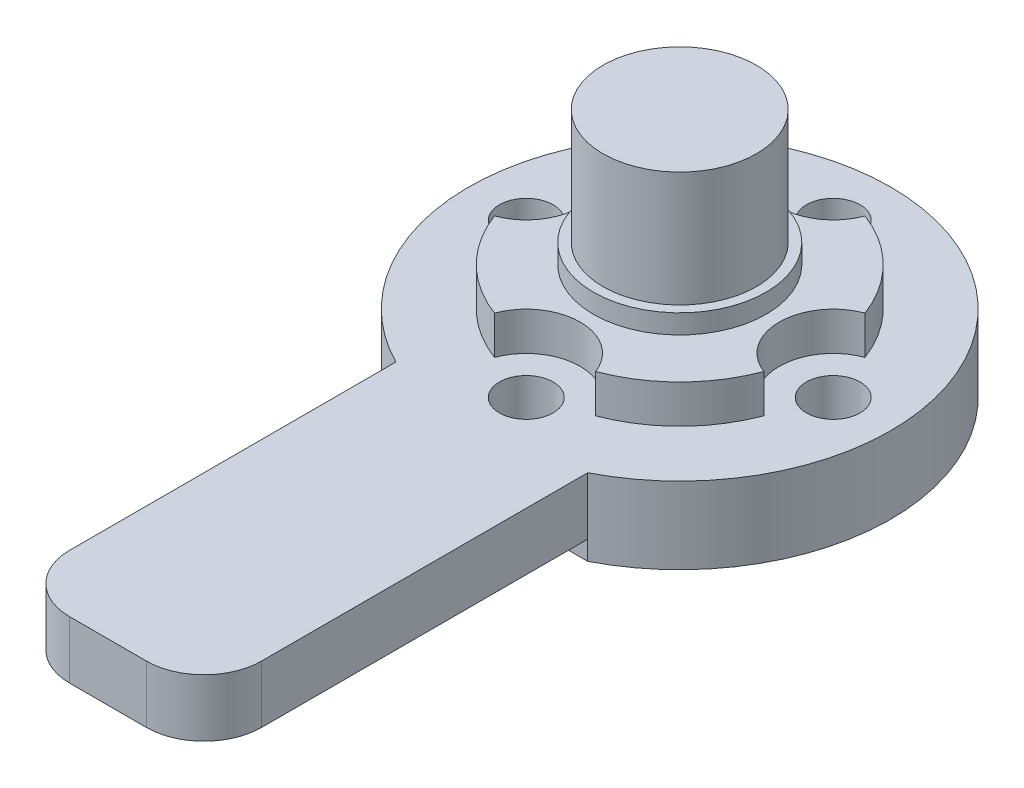
SolidWorks part; units mm, degrees
ref_plane "Front Plane" through (0, 0, 0) normal (0, 0, 1) x (1, 0, 0)
ref_plane "Top Plane" through (0, 0, 0) normal (0, 1, 0) x (1, 0, 0)
ref_plane "Right Plane" through (0, 0, 0) normal (1, 0, 0) x (0, 0, -1)
sketch "Sketch1" plane through (0, 0, 0) normal (0, 1, 0) x (1, 0, 0)
  circle A0 centre (0, 0) radius 11
  circle A1 centre (0, 0) radius 4.25
  dimension "D1" = 22
  dimension "D2" = 8.5
extrude "Boss-Extrude1" add sketch "Sketch1" along normal blind 4
sketch "Sketch2" plane through (0, 4, 0) normal (0, 1, 0) x (1, 0, 0)
  circle A0 centre (0, 8) radius 1.4
  circle A1 centre (8, 0) radius 1.4
  circle A2 centre (0, -8) radius 1.4
  circle A3 centre (-8, 0) radius 1.4
  point P19 (0, 0)
  dimension "D1" = 2.8
  dimension "D2" = 8
  dimension "D3" = 4
extrude "Cut-Extrude1" cut sketch "Sketch2" against normal through all
sketch "Sketch3" plane through (0, 4, 0) normal (0, 1, 0) x (1, 0, 0)
  circle A0 centre (0, 0) radius 7.5
  dimension "D1" = 15
extrude "Boss-Extrude2" add sketch "Sketch3" along normal blind 2
sketch "Sketch4" plane through (0, 6, 0) normal (0, 1, 0) x (1, 0, 0)
  circle A0 centre (8, 0) radius 2.8111
  circle A1 centre (0, -8) radius 2.8111
  circle A2 centre (-8, 0) radius 2.8111
  circle A3 centre (0, 8) radius 2.8111
  point P12 (0, 0)
  dimension "D1" = 4
extrude "Cut-Extrude2" cut sketch "Sketch4" against normal up to surface (2 mm away) up to face at (0, 4, 0)
sketch "Sketch5" plane through (0, 6, 0) normal (0, 1, 0) x (1, 0, 0)
  circle A0 centre (0, 0) radius 4.5
  dimension "D1" = 9
extrude "Boss-Extrude3" add sketch "Sketch5" along normal blind 7
sketch "Sketch6" plane through (0, 13, 0) normal (0, 1, 0) x (1, 0, 0)
  circle A0 centre (0, 0) radius 4
  circle A1 centre (0, 0) radius 4.5
  dimension "D1" = 8
extrude "Cut-Extrude3" cut sketch "Sketch6" against normal blind 6
sketch "Sketch8" plane through (0, 0, 0) normal (0, -1, 0) x (1, 0, 0)
  line L0 (-5, 29.798) -> (-5, 9.798)
  line L1 (-5, 29.798) -> (5, 29.798)
  line L2 (5, 29.798) -> (5, 9.798)
  circle A0 centre (0, 0) radius 11 construction
  circle A1 centre (0, 0) radius 11
  circle M7 centre (0, 0) radius 11
  dimension "D1" = 10
  dimension "D2" = 20
extrude "Boss-Extrude4" add sketch "Sketch8" against normal up to surface (4 mm away) contours L2 L1 L0 M7 up to face at (0, 4, 0)
sketch "Sketch11" plane through (-5, 0, 0) normal (-1, 0, 0) x (0, 0, 1)
  line L0 (29.798, 4) -> (29.798, 0) construction
  line L1 (9.798, 0) -> (29.798, 0)
  line L2 (9.798, 0) -> (9.798, 1)
  line L3 (9.798, 1) -> (29.798, 1)
  line L4 (29.798, 0) -> (29.798, 1)
  line L5 (19.798, 1) -> (19.798, 0) construction
  line L6 (9.798, 0.5) -> (29.798, 0.5) construction
  point P108 (19.798, 0.5)
  dimension "D1" = 1
extrude "Cut-Extrude5" cut sketch "Sketch11" against normal through all
fillet "Fillet1" radius 3 2 edges at (5, 2.5, 29.798) (-5, 2.5, 29.798)
